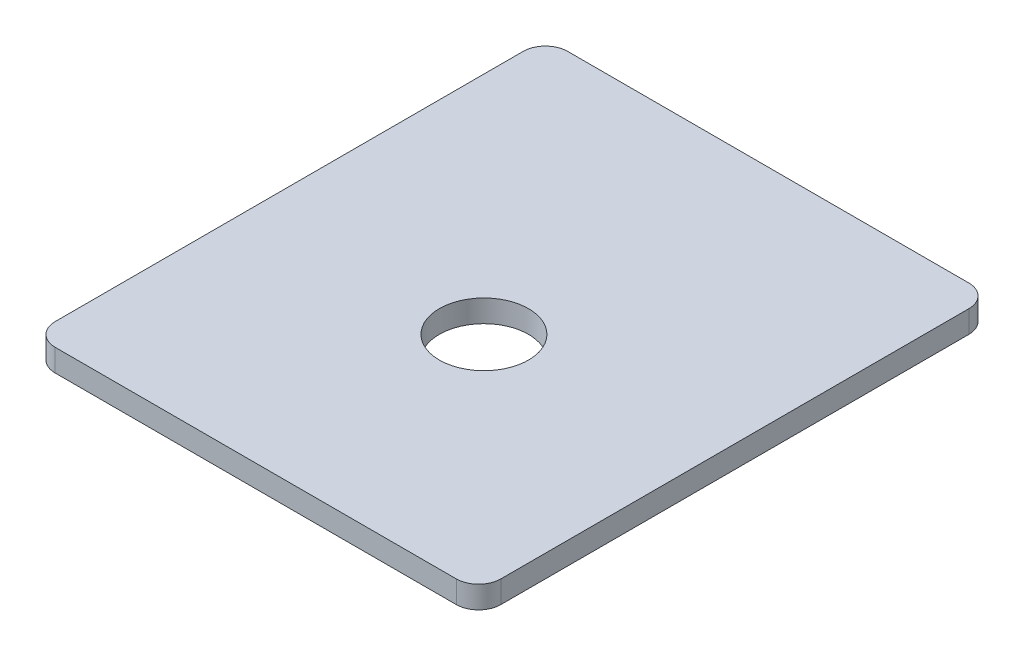
SolidWorks part; units mm, degrees
ref_plane "Front Plane" through (0, 0, 0) normal (0, 0, 1) x (1, 0, 0)
ref_plane "Top Plane" through (0, 0, 0) normal (0, 1, 0) x (1, 0, 0)
ref_plane "Right Plane" through (0, 0, 0) normal (1, 0, 0) x (0, 0, -1)
sketch "Sketch1" plane through (0, 0, 0) normal (0, 1, 0) x (1, 0, 0)
  line L0 (-20, -21) -> (-20, -27)
  line L1 (-20, -27) -> (20, -27)
  line L2 (20, -21) -> (20, 19)
  line L3 (18, 21) -> (-18, 21)
  line L4 (-20, -21) -> (-20, 19)
  line L5 (20, -21) -> (-20, 21) construction
  line L6 (20, 21) -> (-20, -21) construction
  line L7 (20, -27) -> (20, -21)
  arc A0 (20, 19) -> (18, 21) centre (18, 19) ccw
  arc A1 (-18, 21) -> (-20, 19) centre (-18, 19) ccw
  circle A2 centre (0.2327, -4.7519) radius 4
  point P0 (0, 0)
  dimension "D2" = 2
  dimension "D3" = 8
  dimension "D1" = 40
  dimension "D4" = 6
extrude "Boss-Extrude1" add sketch "Sketch1" along normal blind 2
sketch "Sketch5" plane through (0, 2, 0) normal (0, 1, 0) x (1, 0, 0)
  line L0 (-20, 19) -> (-20, -27) construction
  line L1 (20, -27) -> (-20, -27)
  line L2 (20, -27) -> (20, -25)
  line L3 (20, -25) -> (-20, -25)
  line L4 (-20, -27) -> (-20, -25)
  dimension "D1" = 2
extrude "Boss-Extrude5" add sketch "Sketch5" along normal blind 40
sketch "Sketch8" plane through (-20, 0, 0) normal (-1, 0, 0) x (0, 0, 1)
  line L0 (25, 42) -> (25, 0)
  line L1 (-19, 0) -> (27, 0) construction
  line L2 (25, 0) -> (27, 0)
  line L3 (27, 42) -> (27, 0) construction
  line L4 (27, 0) -> (27, 42)
  line L5 (27, 42) -> (25, 42)
  point P5 (0, 0)
extrude "Cut-Extrude4" cut sketch "Sketch8" along normal through all and the other way blind 52
fillet "Fillet1" radius 2 1 edges at (-20, 1, 25)
fillet "Fillet2" radius 2 1 edges at (20, 1, 25)
